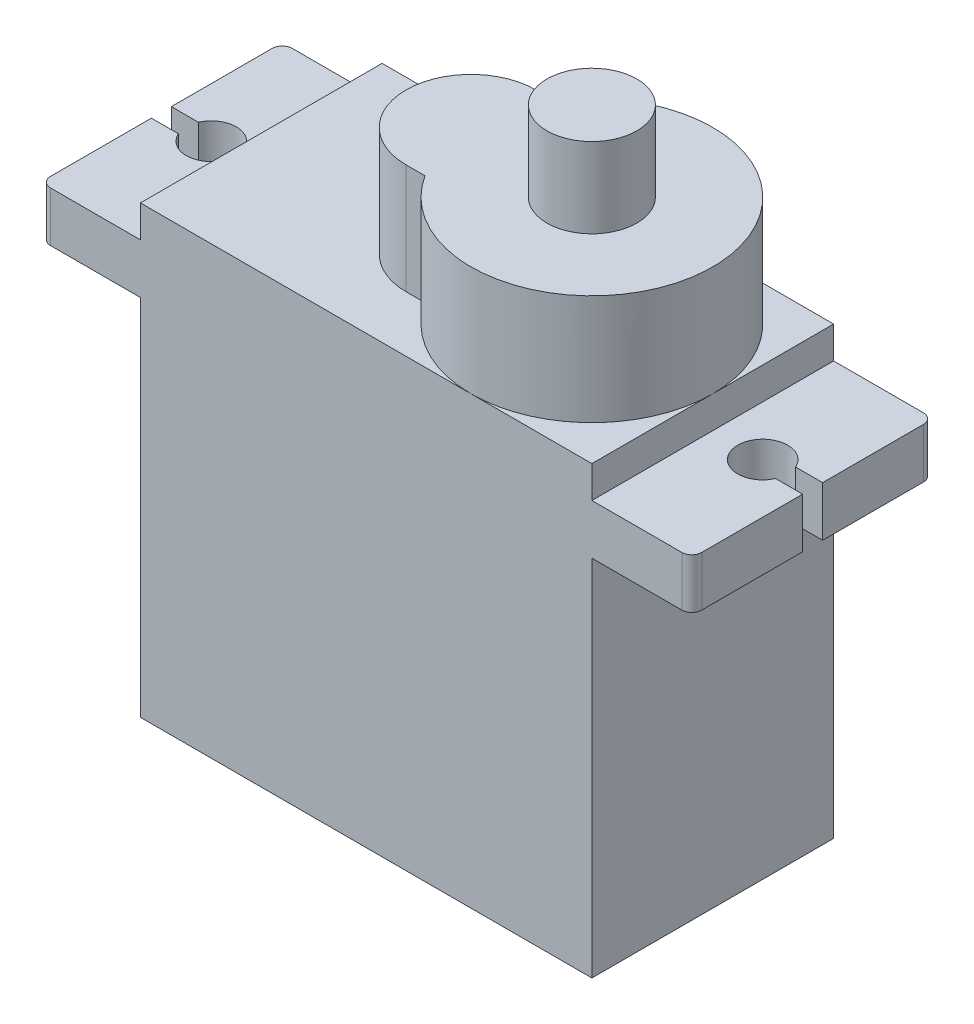
SolidWorks part; units mm, degrees
ref_plane "Front Plane" through (0, 0, 0) normal (0, 0, 1) x (1, 0, 0)
ref_plane "Top Plane" through (0, 0, 0) normal (0, 1, 0) x (1, 0, 0)
ref_plane "Right Plane" through (0, 0, 0) normal (1, 0, 0) x (0, 0, -1)
sketch "Sketch1" plane through (0, 0, 0) normal (0, 1, 0) x (1, 0, 0)
  line L1 (-11.3, -6.05) -> (11.3, -6.05)
  line L2 (-11.3, -6.05) -> (-11.3, 6.05)
  line L3 (-11.3, 6.05) -> (11.3, 6.05)
  line L4 (11.3, -6.05) -> (11.3, 6.05)
  line L5 (-11.3, -6.05) -> (11.3, 6.05) construction
  line L6 (-11.3, 6.05) -> (11.3, -6.05) construction
  point P0 (0, 0)
  dimension "D1" = 12.1
  dimension "D2" = 22.6
extrude "Boss-Extrude1" add sketch "Sketch1" along normal blind 22.3
sketch "Sketch2" plane through (11.3, 0, 0) normal (1, 0, 0) x (0, 0, -1)
  line L0 (0, 0) -> (0, 18.2) construction
  line L1 (-6.05, 18.2) -> (6.05, 18.2)
  line L2 (6.05, 22.3) -> (6.05, 0) construction
  line L3 (-6.05, 18.2) -> (-6.05, 20.7)
  line L4 (-6.05, 22.3) -> (-6.05, 0) construction
  line L5 (-6.05, 20.7) -> (6.05, 20.7)
  line L6 (6.05, 20.7) -> (6.05, 18.2)
  point P8 (0, 18.2)
  dimension "D1" = 18.2
  dimension "D2" = 2.5
extrude "Boss-Extrude2" add sketch "Sketch2" along normal blind 5
mirror "Mirror1" about plane through (0, 0, 0) normal (1, 0, 0) of "Boss-Extrude2"
sketch "Sketch3" plane through (0, 22.3, 0) normal (0, 1, 0) x (1, 0, 0)
  line L0 (11.3, 0) -> (5.25, 0) construction
  line L1 (11.3, -6.05) -> (11.3, 6.05) construction
  line L2 (-0.8, -3.25) -> (-0.8, 3.25)
  line L3 (-0.8, 3.25) -> (0.1471, 3.25)
  line L4 (-0.8, -3.25) -> (0.1471, -3.25)
  circle A0 centre (5.25, 0) radius 6.05
  arc A1 (-0.8, -3.25) -> (-0.8, 3.25) centre (-0.8, 0) cw
  point P9 (-0.8, 0)
  dimension "D3" = 3.25
  dimension "D1" = 6.05
  dimension "D2" = 6.5
extrude "Boss-Extrude3" add sketch "Sketch3" along normal blind 5.5
sketch "Sketch4" plane through (0, 27.8, 0) normal (0, 1, 0) x (1, 0, 0)
  circle A0 centre (5.25, 0) radius 2.25
  dimension "D1" = 4.5
extrude "Boss-Extrude4" add sketch "Sketch4" along normal blind 4
sketch "Sketch6" plane through (0, 20.7, 0) normal (0, 1, 0) x (1, 0, 0)
  line L0 (16.3, 0) -> (11.3, 0) construction
  line L1 (16.3, 6.05) -> (16.3, -6.05) construction
  line L2 (16.3, -0.5) -> (16.3, 0.5)
  line L3 (16.3, 0.5) -> (14.9456, 0.5)
  line L4 (16.3, -0.5) -> (14.9456, -0.5)
  arc A0 (0.1471, -3.25) -> (0.1471, 3.25) centre (5.25, 0) ccw construction
  circle A1 centre (13.8, 0) radius 1.25
  point P12 (16.3, 0)
  line M5 (16.3, -6.05) -> (16.3, 6.05)
  dimension "D1" = 2.5
  dimension "D2" = 1
extrude "Cut-Extrude1" cut sketch "Sketch6" against normal up to next contours L0 A1 L4 M5 | L0 L2 L3 A1 | L0 A1 | A1 L0
mirror "Mirror2" about plane through (0, 0, 0) normal (1, 0, 0) of "Cut-Extrude1"
fillet "Fillet1" radius 0.5 4 edges at (-16.3, 19.45, 6.05) (-16.3, 19.45, -6.05) (16.3, 19.45, -6.05) (16.3, 19.45, 6.05)
